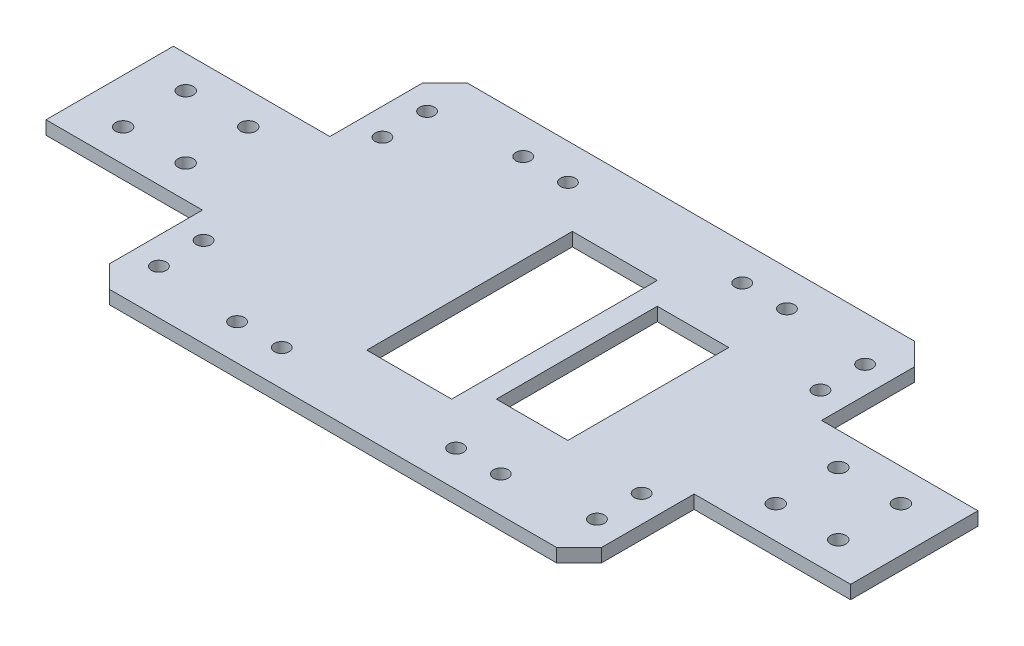
SolidWorks part; units mm, degrees
material "PLA+ esun"
ref_plane "Front Plane" through (0, 0, 0) normal (0, 0, 1) x (1, 0, 0)
ref_plane "Top Plane" through (0, 0, 0) normal (0, 1, 0) x (1, 0, 0)
ref_plane "Right Plane" through (0, 0, 0) normal (1, 0, 0) x (0, 0, -1)
sketch "Sketch1" plane through (0, 0, 0) normal (0, 1, 0) x (1, 0, 0)
  line L0 (0, 0) -> (0, -22.4966) construction
  line L1 (-100, 40) -> (100, 40)
  line L2 (-100, 40) -> (-100, -40)
  line L3 (-100, -40) -> (100, -40)
  line L4 (100, 40) -> (100, -40)
  line L5 (-100, 40) -> (100, -40) construction
  line L6 (-100, -40) -> (100, 40) construction
  line L7 (-9.5, 23) -> (9.5, 23)
  line L8 (-9.5, 23) -> (-9.5, -23)
  line L9 (-9.5, -23) -> (9.5, -23)
  line L10 (9.5, 23) -> (9.5, -23)
  line L11 (-9.5, 23) -> (9.5, -23) construction
  line L12 (-9.5, -23) -> (9.5, 23) construction
  line L13 (-90, 14.25) -> (-56, 14.25)
  line L14 (-90, 14.25) -> (-90, -14.25)
  line L15 (-90, -14.25) -> (-56, -14.25)
  line L16 (-56, 14.25) -> (-56, -14.25)
  line L17 (-90, 14.25) -> (-56, -14.25) construction
  line L18 (-90, -14.25) -> (-56, 14.25) construction
  line L19 (-80, 7) -> (-66, 7)
  line L20 (-80, 7) -> (-80, -7)
  line L21 (-80, -7) -> (-66, -7)
  line L22 (-66, 7) -> (-66, -7)
  line L23 (-80, 7) -> (-66, -7) construction
  line L24 (-80, -7) -> (-66, 7) construction
  line L25 (80, -7) -> (66, 7) construction
  line L26 (80, 7) -> (66, -7) construction
  line L27 (90, -14.25) -> (56, 14.25) construction
  line L28 (90, 14.25) -> (56, -14.25) construction
  line L29 (100, -40) -> (-100, 40) construction
  line L30 (100, 40) -> (-100, -40) construction
  line L31 (66, 7) -> (66, -7)
  line L32 (80, -7) -> (66, -7)
  line L33 (80, 7) -> (80, -7)
  line L34 (80, 7) -> (66, 7)
  line L35 (56, 14.25) -> (56, -14.25)
  line L36 (90, -14.25) -> (56, -14.25)
  line L37 (90, 14.25) -> (90, -14.25)
  line L38 (90, 14.25) -> (56, 14.25)
  line L39 (-100, -30.3979) -> (-77.5, -30.3979) construction
  line L40 (-77.5, -30.3979) -> (-55, -30.3979) construction
  line L41 (0, 0) -> (18.7357, 0) construction
  line L42 (-100, -40) -> (-55, -40)
  line L43 (-100, -40) -> (-100, -14.25)
  line L44 (-100, -14.25) -> (-55, -14.25)
  line L45 (-55, -40) -> (-55, -14.25)
  line L46 (55, -40) -> (55, -14.25)
  line L47 (100, -14.25) -> (55, -14.25)
  line L48 (-100, 14.25) -> (-55, 14.25)
  line L49 (100, 14.25) -> (55, 14.25)
  line L50 (55, 40) -> (55, 14.25)
  line L51 (-55, 40) -> (-55, 14.25)
  line L57 (14.5, 18) -> (30.5, 18)
  line L58 (14.5, 18) -> (14.5, -18)
  line L59 (14.5, -18) -> (30.5, -18)
  line L60 (30.5, 18) -> (30.5, -18)
  circle A1 centre (-80, 7) radius 1.7
  circle A2 centre (-66, 7) radius 1.7
  circle A3 centre (-66, -7) radius 1.7
  circle A4 centre (-80, -7) radius 1.7
  circle A5 centre (-80, 7) radius 2.75
  circle A6 centre (80, 7) radius 2.75
  circle A7 centre (80, -7) radius 1.7
  circle A8 centre (66, -7) radius 1.7
  circle A9 centre (66, 7) radius 1.7
  circle A10 centre (80, 7) radius 1.7
  point P0 (0, 0)
  point P6 (0, 0)
  point P11 (-73, 0)
  point P18 (-73, 0)
  point P44 (73, 0)
  dimension "D9" = 2
  dimension "D10" = 2
  dimension "D13" = 45
  dimension "D2" = 80
  dimension "D3" = 19
  dimension "D4" = 46
  dimension "D5" = 34
  dimension "D6" = 28.5
  dimension "D7" = 25.75
  dimension "D8" = 10
  dimension "D11" = 14
  dimension "D12" = 14
  dimension "D14" = 22.5
  dimension "D15" = 200
  dimension "D16" = 25.75
  dimension "D17" = 5
  dimension "D18" = 5
  dimension "D19" = 5
  dimension "D20" = 16
extrude "Boss-Extrude1" add sketch "Sketch1" along normal blind 3 contours L4 L1 L2 L3 L38 L37 L36 L35 L7 L10 L9 L8 L13 L16 L15 L14 | L16 L13 L14 L15 A5 L19 A2 L22 A3 L21 A4 L20 | L37 L38 L35 L36 L31 A9 L34 A6 L33 A7 L32 A8 | L19 A5 L20 A1 | L34 A10 L33 A6 | A5 L20 A4 L21 A3 L22 A2 L19 | L20 A5 L19 A1 | L34 A9 L31 A8 L32 A7 L33 A6 | L33 A10 L34 A6
sketch "Sketch4" plane through (0, 3, 0) normal (0, 1, 0) x (1, 0, 0)
  line L2 (-9.5, 23) -> (9.5, 23) construction
  line L4 (9.5, 23) -> (9.5, -23) construction
  line L5 (0, 0) -> (38.0714, 0) construction
  line L6 (0, 0) -> (0, -7.3126) construction
  circle A0 centre (29.5, 32) radius 1.65
  circle A1 centre (19.5, 32) radius 1.65
  circle A2 centre (19.5, -32) radius 1.65
  circle A3 centre (29.5, -32) radius 1.65
  circle A4 centre (-19.5, 32) radius 1.65
  circle A5 centre (-29.5, 32) radius 1.65
  circle A6 centre (-29.5, -32) radius 1.65
  circle A7 centre (-19.5, -32) radius 1.65
  dimension "D1" = 3.3
  dimension "D2" = 9
  dimension "D3" = 20
  dimension "D5" = 10
  dimension "D4" = 2
extrude "Cut-Extrude2" cut sketch "Sketch4" against normal blind 15
sketch "Sketch5" plane through (0, 3, 0) normal (0, 1, 0) x (1, 0, 0)
  line L8 (-55, 40) -> (-55, 14.25) construction
  line L9 (-55, 40) -> (55, 40) construction
  circle A0 centre (-49, 30) radius 1.65
  circle A1 centre (-49, -20) radius 1.65
  circle A2 centre (-49, -30) radius 1.65
  circle A3 centre (-49, 20) radius 1.65
  circle A4 centre (49, 20) radius 1.65
  circle A5 centre (49, -30) radius 1.65
  circle A6 centre (49, -20) radius 1.65
  circle A7 centre (49, 30) radius 1.65
  point P0 (0, 0)
  dimension "D1" = 3.3
  dimension "D2" = 6
  dimension "D3" = 10
  dimension "D5" = 10
  dimension "D4" = 2
extrude "Cut-Extrude3" cut sketch "Sketch5" against normal blind 10
chamfer "Chamfer1" distance 5 angle 45 4 edges at (-55, 1.5, -40) (55, 1.5, -40) (55, 1.5, 40) (-55, 1.5, 40)
